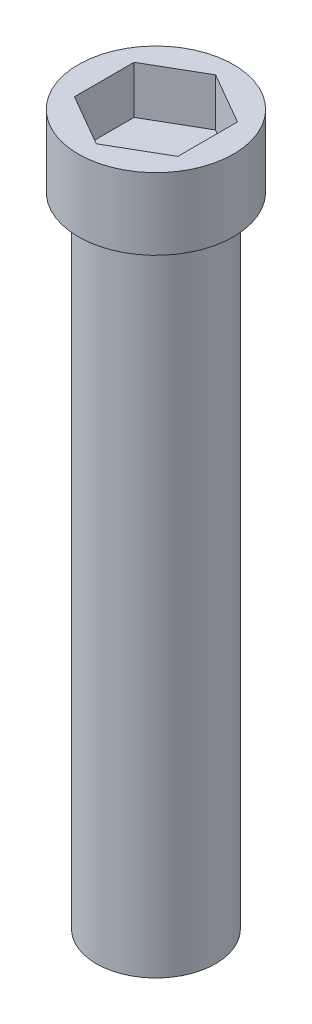
SolidWorks part; units mm, degrees
material "Cast Alloy Steel"
ref_plane "Front Plane" through (0, 0, 0) normal (0, 0, 1) x (1, 0, 0)
ref_plane "Top Plane" through (0, 0, 0) normal (0, 1, 0) x (1, 0, 0)
ref_plane "Right Plane" through (0, 0, 0) normal (1, 0, 0) x (0, 0, -1)
sketch "Sketch1" plane through (0, 0, 0) normal (0, 1, 0) x (1, 0, 0)
  circle A0 centre (0, 0) radius 2.5
  dimension "D1" = 5
extrude "Screw Length" add sketch "Sketch1" along normal blind 26.75
sketch "Sketch2" plane through (0, 26.75, 0) normal (0, 1, 0) x (1, 0, 0)
  circle A0 centre (0, 0) radius 3.25
  dimension "D1" = 6.5
extrude "Screw Cap" add sketch "Sketch2" along normal blind 3
sketch "Sketch3" plane through (0, 29.75, 0) normal (0, 1, 0) x (1, 0, 0)
  line L1 (0, 2.5) -> (-2.1651, 1.25)
  line L2 (-2.1651, 1.25) -> (-2.1651, -1.25)
  line L3 (-2.1651, -1.25) -> (0, -2.5)
  line L4 (0, -2.5) -> (2.1651, -1.25)
  line L5 (2.1651, -1.25) -> (2.1651, 1.25)
  line L6 (2.1651, 1.25) -> (0, 2.5)
  circle A0 centre (0, 0) radius 2.1651 construction
  dimension "D1" = 2.5
extrude "Screw Hole" cut sketch "Sketch3" against normal blind 2
equation "\"D1@Screw Length\"=19.25+4.5+3"
